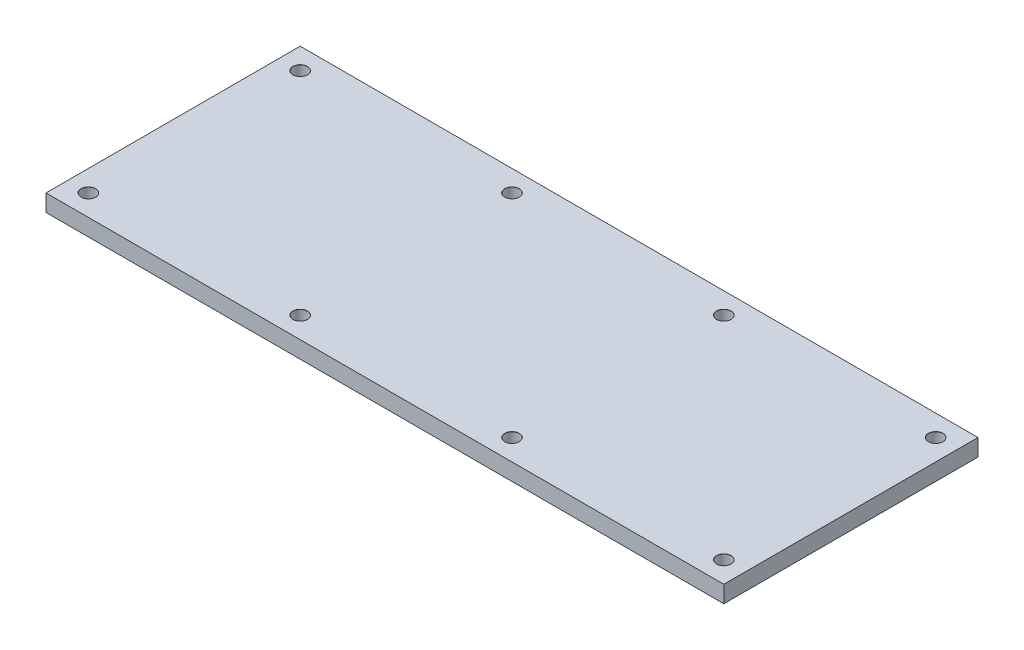
SolidWorks part; units mm, degrees
material "PC High Viscosity"
ref_plane "Front Plane" through (0, 0, 0) normal (0, 0, 1) x (1, 0, 0)
ref_plane "Top Plane" through (0, 0, 0) normal (0, 1, 0) x (1, 0, 0)
ref_plane "Right Plane" through (0, 0, 0) normal (1, 0, 0) x (0, 0, -1)
sketch "Sketch1" plane through (0, 0, 0) normal (0, 1, 0) x (1, 0, 0)
  line L1 (0, 0) -> (160, 0)
  line L2 (0, 0) -> (0, 60)
  line L3 (0, 60) -> (160, 60)
  line L4 (160, 0) -> (160, 60)
  dimension "D1" = 60
  dimension "D2" = 160
extrude "Boss-Extrude1" add sketch "Sketch1" along normal blind 4
sketch "Sketch2" plane through (0, 4, 0) normal (0, 1, 0) x (1, 0, 0)
  line L0 (0, 30) -> (90.133, 30) construction
  line L1 (0, 60) -> (0, 0) construction
  point P6 (5, 5)
  point P14 (55, 5)
  point P15 (105, 5)
  point P16 (155, 5)
  point P21 (5, 55)
  point P22 (55, 55)
  point P23 (105, 55)
  point P24 (155, 55)
  dimension "D1" = 25
  dimension "D3" = 5
  dimension "D2" = 4
  dimension "D4" = 2
hole_wizard "M3 Clearance Hole1" positions "Sketch2" profile "Sketch3" hole size "M3" standard "DIN" end condition up to next
sketch "Sketch3" plane through (155, 4, -55) normal (1, 0, 0) x (0, 0, 1)
  line L0 (0, 0) -> (0, 4)
  line L1 (0, 4) -> (1.7, 4)
  line L2 (1.7, 4) -> (1.7, 0.025)
  line L3 (1.7, 0.025) -> (1.725, 0)
  line L5 (1.725, 0) -> (0, 0)
  line L6 (-1.7, 0.025) -> (-1.725, 0) construction
  line L11 (0, -6.35) -> (0, 107.95) construction
  dimension "Thru Hole Dia." = 3.4
  dimension "Thru Hole Depth" = 4
  dimension "Near C'Sink Dia." = 3.45
  dimension "Near C'Sink Angle" = 90
